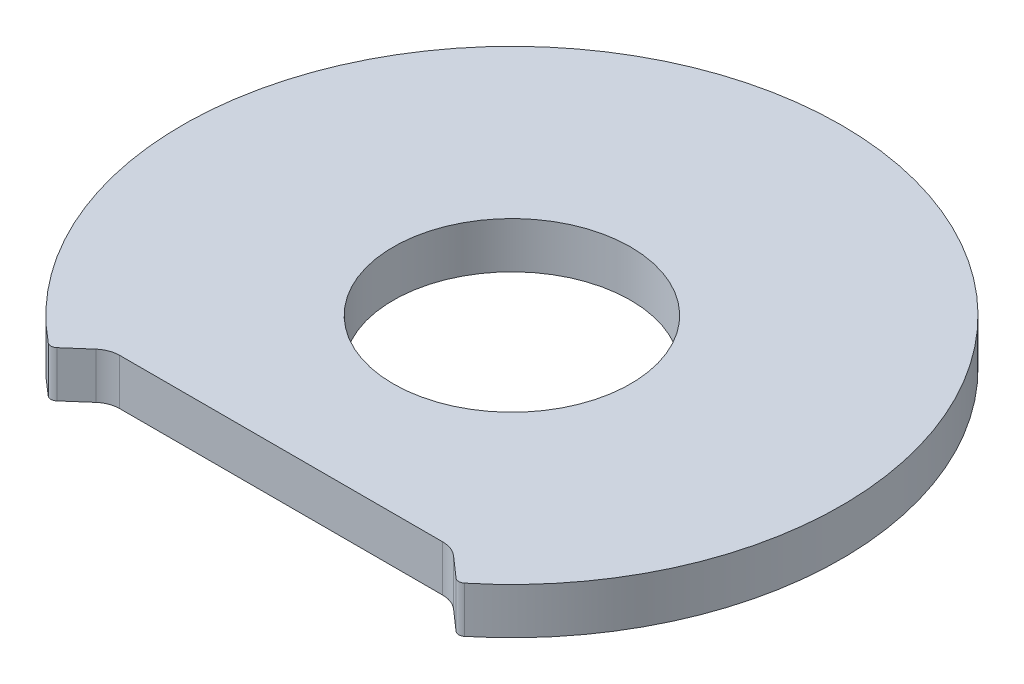
SolidWorks part; units mm, degrees
ref_plane "Front Plane" through (0, 0, 0) normal (0, 0, 1) x (1, 0, 0)
ref_plane "Top Plane" through (0, 0, 0) normal (0, 1, 0) x (1, 0, 0)
ref_plane "Right Plane" through (0, 0, 0) normal (1, 0, 0) x (0, 0, -1)
sketch "Sketch1" plane through (0, 0, 0) normal (0, 1, 0) x (1, 0, 0)
  line L0 (0, 50) -> (0, -35) construction
  line L1 (24.5, -35) -> (-24.5, -35)
  line L2 (-27.141, -35.9958) -> (-30.2752, -38.7511)
  line L3 (27.141, -35.9958) -> (30.2752, -38.7511)
  arc A0 (31.5668, -38.7755) -> (-31.5668, -38.7755) centre (0, 0) ccw
  circle A1 centre (0, 0) radius 18
  arc A2 (-24.5, -35) -> (-27.141, -35.9958) centre (-24.5, -39) ccw
  arc A3 (24.5, -35) -> (27.141, -35.9958) centre (24.5, -39) cw
  arc A4 (-30.2752, -38.7511) -> (-31.5668, -38.7755) centre (-30.9354, -38) cw
  arc A5 (30.2752, -38.7511) -> (31.5668, -38.7755) centre (30.9354, -38) ccw
  point P1 (26.5664, -33.652)
  point P16 (0, -35)
  dimension "D1" = 100
  dimension "D2" = 36
  dimension "D3" = 1
  dimension "D4" = 4
  dimension "D5" = 4
  dimension "D6" = 49
  dimension "D7" = 85
extrude "Boss-Extrude1" add sketch "Sketch1" along normal blind 7
